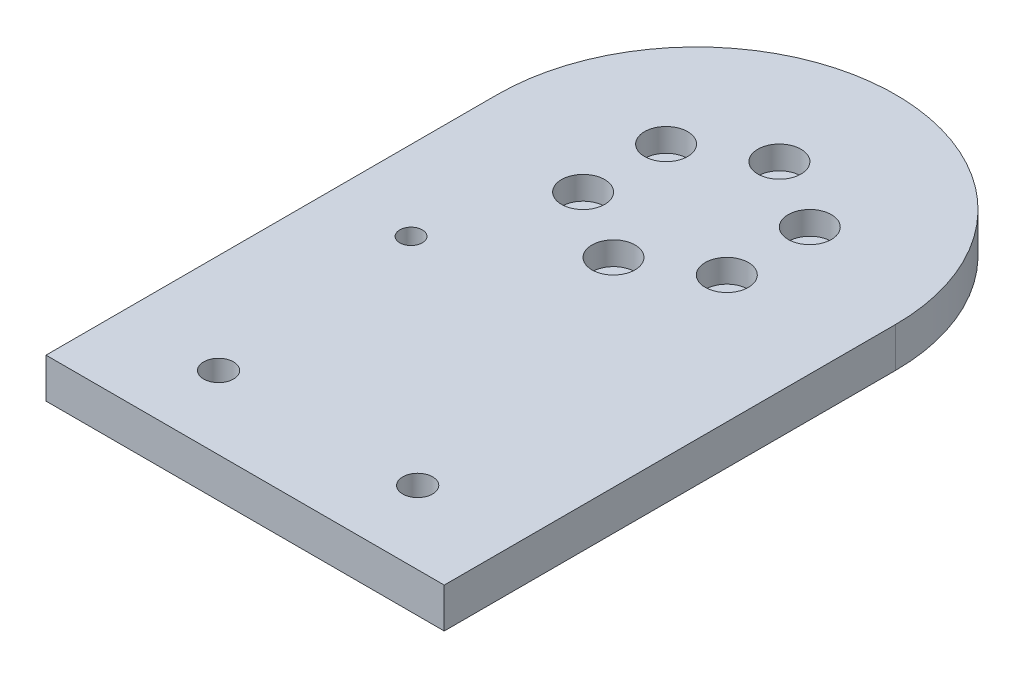
SolidWorks part; units mm, degrees
material "Aleación 6061"
ref_plane "Alzado" through (0, 0, 0) normal (0, 0, 1) x (1, 0, 0)
ref_plane "Planta" through (0, 0, 0) normal (0, 1, 0) x (1, 0, 0)
ref_plane "Vista lateral" through (0, 0, 0) normal (1, 0, 0) x (0, 0, -1)
sketch "Sk_Placa" plane through (0, 0, 0) normal (0, 1, 0) x (1, 0, 0)
  line L1 (-30, -379) -> (30, -379)
  line L2 (-30, -379) -> (-30, -330)
  line L3 (-30, -330) -> (30, -330)
  line L4 (30, -379) -> (30, -330)
  line L5 (-30, -379) -> (30, -330) construction
  line L6 (-30, -330) -> (30, -379) construction
  point P0 (0, -354.5)
  dimension "D1" = 60
  dimension "D2" = 49
  dimension "D3" = 354.5
extrude "Placa" add sketch "Sk_Placa" along normal blind 6 from offset 59.75
sketch "Sk_Extremo" plane through (0, 0, 0) normal (0, 1, 0) x (1, 0, 0)
  circle A0 centre (0, -330) radius 30
  dimension "D1" = 60
  dimension "D2" = 330
extrude "Extremo" add sketch "Sk_Extremo" along normal blind 6 from offset 59.75
sketch "Sk_Pasantes_M3_cubo_J3" plane through (0, 0, 0) normal (0, 1, 0) x (1, 0, 0)
  circle A0 centre (10.8253, -336.25) radius 1.7
  circle A1 centre (0, -342.5) radius 1.7
  circle A2 centre (-10.8253, -336.25) radius 1.7
  circle A3 centre (-10.8253, -323.75) radius 1.7
  circle A4 centre (0, -317.5) radius 1.7
  circle A5 centre (10.8253, -323.75) radius 1.7
  dimension "D1" = 3.4
  dimension "D4" = 3.4
  dimension "D6" = 3.4
  dimension "D9" = 3.4
  dimension "D12" = 3.4
  dimension "D14" = 3.4
  dimension "D2" = 10.8253
  dimension "D3" = 336.25
  dimension "D5" = 342.5
  dimension "D7" = 10.8253
  dimension "D8" = 336.25
  dimension "D10" = 10.8253
  dimension "D11" = 323.75
  dimension "D13" = 317.5
  dimension "D15" = 10.8253
  dimension "D16" = 323.75
extrude "Pasantes_M3_cubo_J3" cut sketch "Sk_Pasantes_M3_cubo_J3" along normal blind 6 from offset 59.75
sketch "Sk_Cajas_M3_J3" plane through (0, 0, 0) normal (0, 1, 0) x (1, 0, 0)
  circle A0 centre (10.8253, -336.25) radius 3.25
  circle A1 centre (0, -342.5) radius 3.25
  circle A2 centre (-10.8253, -336.25) radius 3.25
  circle A3 centre (-10.8253, -323.75) radius 3.25
  circle A4 centre (0, -317.5) radius 3.25
  circle A5 centre (10.8253, -323.75) radius 3.25
  dimension "D1" = 6.5
  dimension "D4" = 6.5
  dimension "D6" = 6.5
  dimension "D9" = 6.5
  dimension "D12" = 6.5
  dimension "D14" = 6.5
  dimension "D2" = 10.8253
  dimension "D3" = 336.25
  dimension "D5" = 342.5
  dimension "D7" = 10.8253
  dimension "D8" = 336.25
  dimension "D10" = 10.8253
  dimension "D11" = 323.75
  dimension "D13" = 317.5
  dimension "D15" = 10.8253
  dimension "D16" = 323.75
extrude "Cajas_M3_J3" cut sketch "Sk_Cajas_M3_J3" along normal blind 3.5 from offset 62.25
sketch "Sk_Extension_pestanas" plane through (0, 0, 0) normal (0, 1, 0) x (1, 0, 0)
  line L1 (-30, -398) -> (30, -398)
  line L2 (-30, -398) -> (-30, -379)
  line L3 (-30, -379) -> (30, -379)
  line L4 (30, -398) -> (30, -379)
  line L5 (-30, -398) -> (30, -379) construction
  line L6 (-30, -379) -> (30, -398) construction
  point P0 (0, -388.5)
  dimension "D1" = 60
  dimension "D2" = 19
  dimension "D3" = 388.5
extrude "Extension_pestanas" add sketch "Sk_Extension_pestanas" along normal blind 6 from offset 59.75
sketch "Sk_Pasantes_M4_repisa" plane through (0, 0, 0) normal (0, 1, 0) x (1, 0, 0)
  circle A0 centre (-15, -387) radius 2.25
  circle A1 centre (15, -387) radius 2.25
  dimension "D1" = 4.5
  dimension "D4" = 4.5
  dimension "D2" = 15
  dimension "D3" = 387
  dimension "D5" = 15
  dimension "D6" = 387
extrude "Pasantes_M4_repisa" cut sketch "Sk_Pasantes_M4_repisa" along normal blind 6 from offset 59.75
sketch "Sk_Pasante_M3_cincho" plane through (0, 0, 0) normal (0, 1, 0) x (1, 0, 0)
  circle A0 centre (-18, -355) radius 1.7
  dimension "D1" = 3.4
  dimension "D2" = 18
  dimension "D3" = 355
extrude "Pasante_M3_cincho" cut sketch "Sk_Pasante_M3_cincho" along normal blind 6 from offset 59.75
